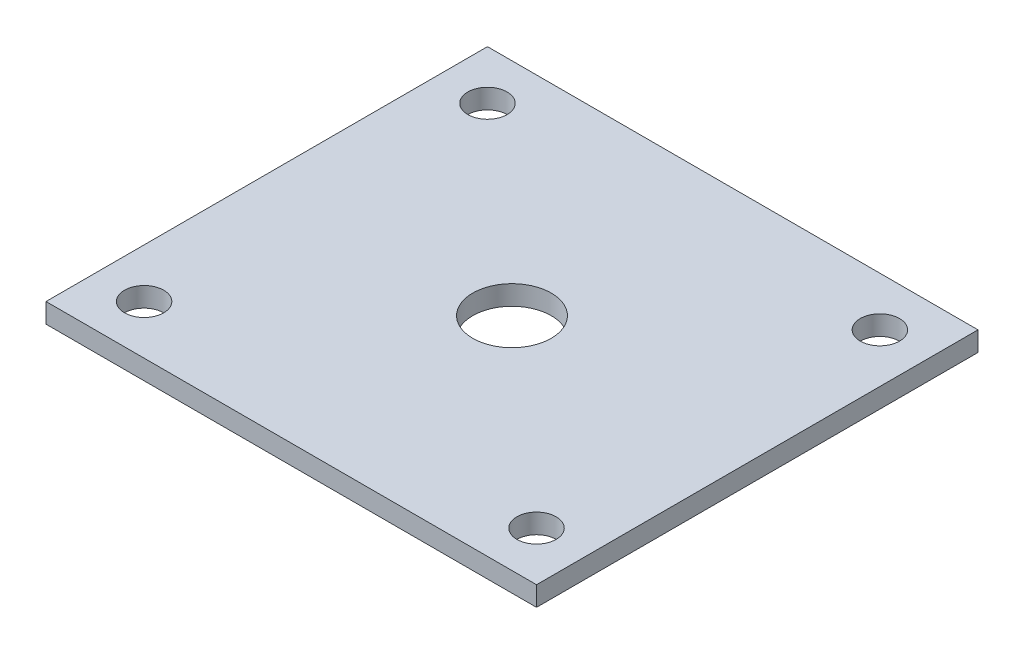
SolidWorks part; units mm, degrees
ref_plane "前视" through (0, 0, 0) normal (0, 0, 1) x (1, 0, 0)
ref_plane "上视" through (0, 0, 0) normal (0, 1, 0) x (1, 0, 0)
ref_plane "右视" through (0, 0, 0) normal (1, 0, 0) x (0, 0, -1)
sketch "Sketch1" plane through (0, 0, 0) normal (0, 1, 0) x (1, 0, 0)
  line L1 (0, 0) -> (100, 0)
  line L2 (0, 0) -> (0, 90)
  line L3 (0, 90) -> (100, 90)
  line L4 (100, 0) -> (100, 90)
  circle A0 centre (50, 45) radius 8
  circle A1 centre (10, 80) radius 4
  circle A2 centre (10, 10) radius 4
  circle A3 centre (90, 10) radius 4
  circle A4 centre (90, 80) radius 4
  dimension "D3" = 50
  dimension "D4" = 10
  dimension "D8" = 45
  dimension "D1" = 90
  dimension "D2" = 100
  dimension "D5" = 10
  dimension "D6" = 10
  dimension "D7" = 10
  dimension "D9" = 2
extrude "Extrude1" add sketch "Sketch1" along normal blind 4
